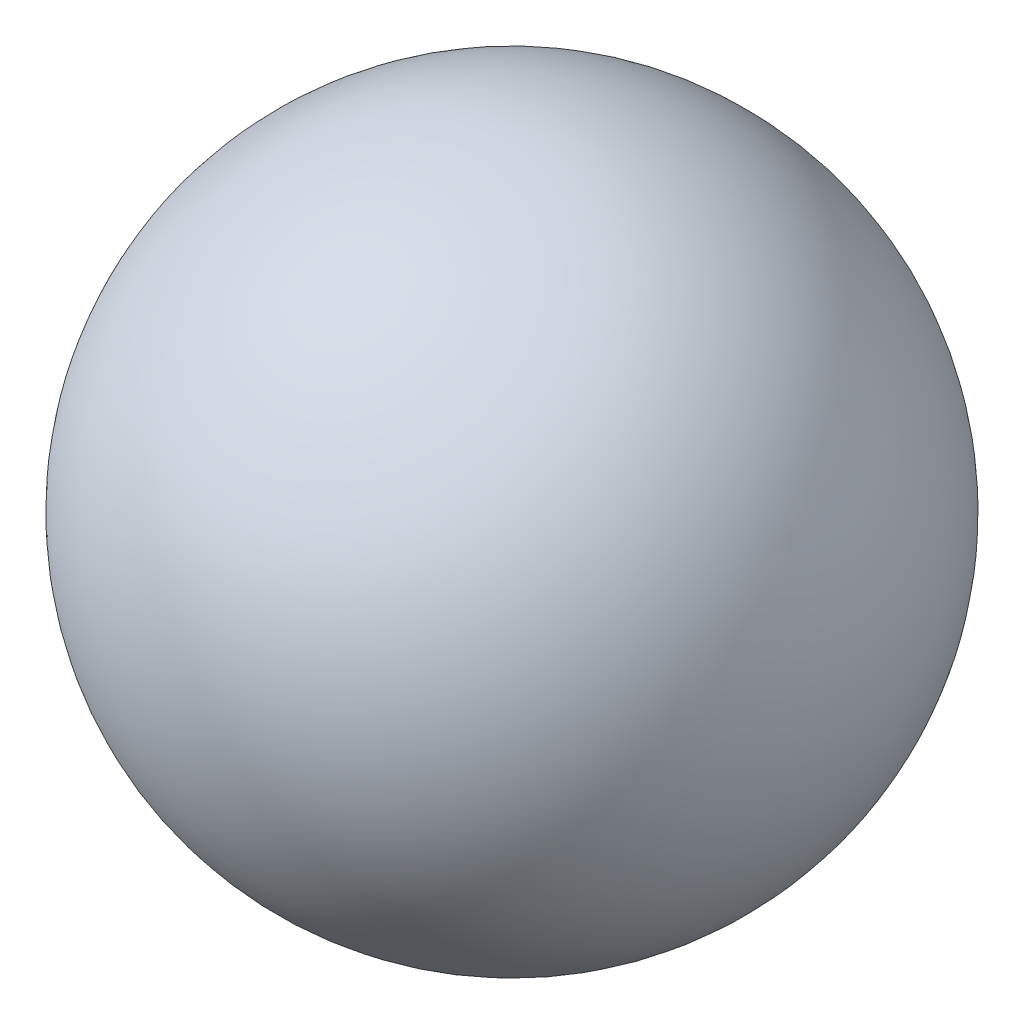
SolidWorks part; units mm, degrees
ref_plane "Alzado" through (0, 0, 0) normal (0, 0, 1) x (1, 0, 0)
ref_plane "Planta" through (0, 0, 0) normal (0, 1, 0) x (1, 0, 0)
ref_plane "Vista lateral" through (0, 0, 0) normal (1, 0, 0) x (0, 0, -1)
sketch "Croquis1" plane through (0, 0, 0) normal (0, 0, 1) x (1, 0, 0)
  line L0 (-9.5, 0) -> (9.5, 0) construction
  line L1 (-9.5, 0) -> (9.5, 0)
  arc A0 (-9.5, 0) -> (9.5, 0) centre (0, 0) ccw
  dimension "D2" = 9.5
revolve "Revolución1" add sketch "Croquis1" angle 360 about L0
